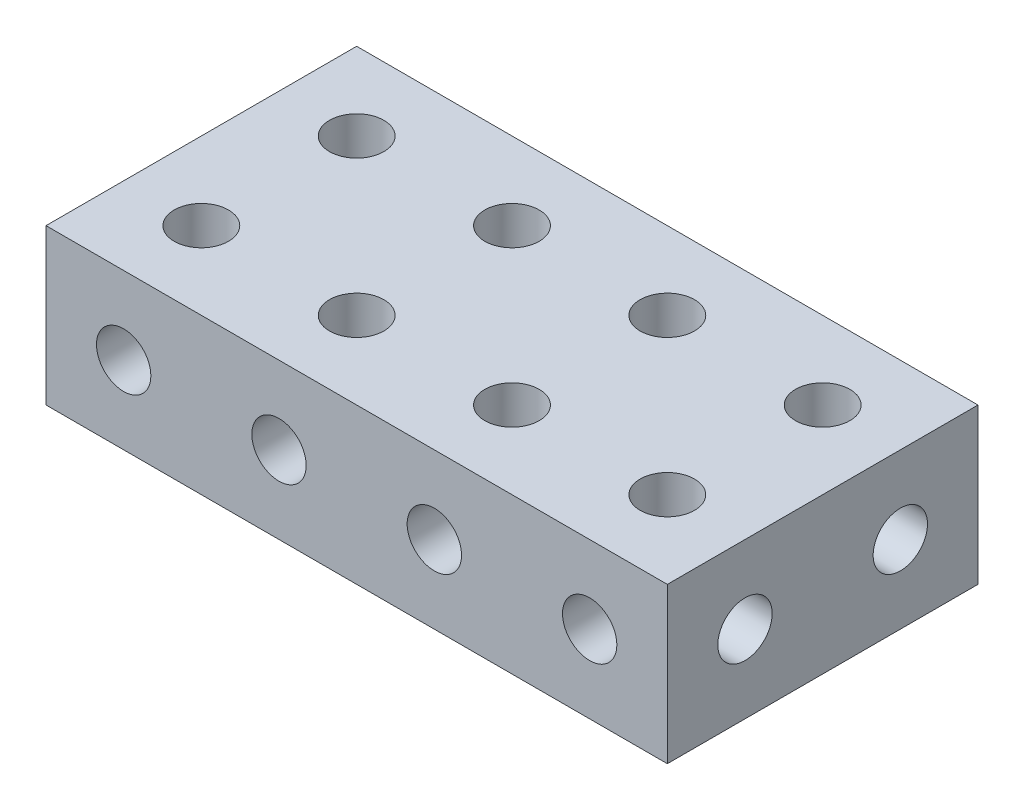
SolidWorks part; units mm, degrees
ref_plane "Plan de face" through (0, 0, 0) normal (0, 0, 1) x (1, 0, 0)
ref_plane "Plan de dessus" through (0, 0, 0) normal (0, 1, 0) x (1, 0, 0)
ref_plane "Plan de droite" through (0, 0, 0) normal (1, 0, 0) x (0, 0, -1)
sketch "Esquisse1" plane through (0, 0, 0) normal (1, 0, 0) x (0, 0, -1)
  line L1 (0, 0) -> (20, 0)
  line L2 (0, 0) -> (0, 10)
  line L3 (0, 10) -> (20, 10)
  line L4 (20, 0) -> (20, 10)
  dimension "D1" = 20
  dimension "D2" = 10
extrude "Boss.-Extru.1" add sketch "Esquisse1" along normal blind 40
sketch "Esquisse2" plane through (0, 10, 0) normal (0, 1, 0) x (1, 0, 0)
  line L0 (0, 15) -> (40, 15) construction
  line L4 (40, 20) -> (0, 20) construction
  circle A0 centre (5, 15) radius 1.75
  circle A1 centre (15, 15) radius 1.75
  circle A2 centre (25, 15) radius 1.75
  circle A3 centre (35, 15) radius 1.75
  circle A4 centre (5, 5) radius 1.75
  circle A5 centre (15, 5) radius 1.75
  circle A6 centre (25, 5) radius 1.75
  circle A7 centre (35, 5) radius 1.75
  circle A8 centre (5, -5) radius 1.75
  circle A9 centre (15, -5) radius 1.75
  circle A10 centre (25, -5) radius 1.75
  circle A11 centre (35, -5) radius 1.75
  circle A12 centre (5, -15) radius 1.75
  circle A13 centre (15, -15) radius 1.75
  circle A14 centre (25, -15) radius 1.75
  circle A15 centre (35, -15) radius 1.75
  dimension "D4" = 3.5
  dimension "D1" = 5
  dimension "D2" = 10
  dimension "D3" = 10
  dimension "D5" = 10
  dimension "D6" = 5
  dimension "D7" = 4
extrude "Enlèv. mat.-Extru.1" cut sketch "Esquisse2" against normal through all
sketch "Esquisse3" plane through (0, 0, 0) normal (0, 0, 1) x (1, 0, 0)
  line L0 (0, 5) -> (40, 5) construction
  line L1 (0, 10) -> (0, 0) construction
  line L2 (40, 10) -> (40, 0) construction
  circle A0 centre (5, 5) radius 1.75
  circle A1 centre (15, 5) radius 1.75
  circle A2 centre (25, 5) radius 1.75
  circle A3 centre (35, 5) radius 1.75
  dimension "D4" = 3.5
  dimension "D1" = 5
  dimension "D2" = 10
  dimension "D3" = 10
  dimension "D5" = 10
extrude "Enlèv. mat.-Extru.2" cut sketch "Esquisse3" against normal blind 40
sketch "Esquisse4" plane through (40, 0, 0) normal (1, 0, 0) x (0, 0, -1)
  line L0 (0, 5) -> (20, 5) construction
  line L1 (0, 10) -> (0, 0) construction
  line L2 (20, 0) -> (20, 10) construction
  circle A0 centre (5, 5) radius 1.75
  circle A1 centre (15, 5) radius 1.75
  circle A2 centre (25, 5) radius 1.75
  circle A3 centre (35, 5) radius 1.75
  dimension "D1" = 3.5
  dimension "D2" = 5
  dimension "D3" = 4
extrude "Enlèv. mat.-Extru.3" cut sketch "Esquisse4" against normal blind 40
